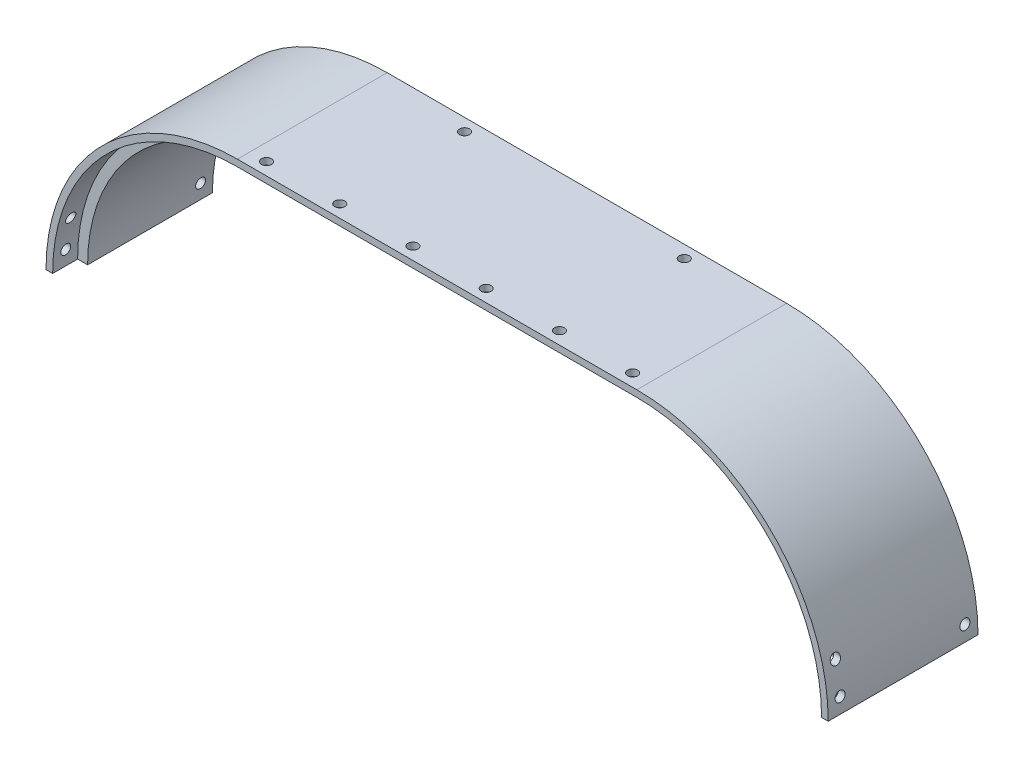
SolidWorks part; units mm, degrees
ref_plane "Front Plane" through (0, 0, 0) normal (0, 0, 1) x (1, 0, 0)
ref_plane "Top Plane" through (0, 0, 0) normal (0, 1, 0) x (1, 0, 0)
ref_plane "Right Plane" through (0, 0, 0) normal (1, 0, 0) x (0, 0, -1)
sketch "Sketch1" plane through (0, 0, 0) normal (0, 0, 1) x (1, 0, 0)
  line L0 (-60, 52.5) -> (60, 52.5)
  line L1 (-60, -52.5) -> (60, -52.5)
  line L2 (-60, 57.5) -> (60, 57.5)
  line L3 (-60, -57.5) -> (60, -57.5)
  line L4 (-130.8088, 0) -> (140.4694, 0)
  arc A0 (-60, 52.5) -> (-60, -52.5) centre (-60, 0) ccw
  arc A1 (60, -52.5) -> (60, 52.5) centre (60, 0) ccw
  arc A2 (60, 52.5) -> (60, -52.5) centre (60, 0) ccw construction
  arc A3 (-60, -52.5) -> (-60, 52.5) centre (-60, 0) ccw construction
  arc A4 (60, -57.5) -> (60, 57.5) centre (60, 0) ccw
  arc A5 (-60, 57.5) -> (-60, -57.5) centre (-60, 0) ccw
  dimension "D1" = 105
  dimension "D2" = 60
  dimension "D3" = 60
  dimension "D4" = 5
extrude "Boss-Extrude1" add sketch "Sketch1" along normal blind 45 contours L2 A5 L4 A0 L0 A1 A4
sketch "Sketch3" plane through (0, 0, 45) normal (0, 0, 1) x (1, 0, 0)
  line L4 (-115.5, 0) -> (115.5, 0)
  line L5 (60, 55.5) -> (-60, 55.5)
  line L6 (60, 55.5) -> (-60, 55.5)
  arc A10 (115.5, 0) -> (60, 55.5) centre (60, 0) ccw
  arc A11 (-60, 55.5) -> (-115.5, 0) centre (-60, 0) ccw
  arc A12 (115.5, 0) -> (60, 55.5) centre (60, 0) ccw
  arc A13 (-60, 55.5) -> (-115.5, 0) centre (-60, 0) ccw
  dimension "D1" = 3
extrude "Cut-Extrude1" cut sketch "Sketch3" against normal blind 7.5
sketch "Sketch4" plane through (0, 57.5, 0) normal (0, 1, 0) x (1, 0, 0)
  line L0 (0, -65.2933) -> (0, 28.2975) construction
  line L1 (-60, 0) -> (60, 0) construction
  line L2 (-60, -45) -> (60, -45) construction
  circle A0 centre (33, -3.75) radius 1.5
  circle A1 centre (11, -41.25) radius 1.5
  circle A2 centre (33, -41.25) radius 1.5
  circle A3 centre (55, -41.25) radius 1.5
  circle A4 centre (-33, -3.75) radius 1.5
  circle A5 centre (-11, -41.25) radius 1.5
  circle A6 centre (-33, -41.25) radius 1.5
  circle A7 centre (-55, -41.25) radius 1.5
  dimension "D1" = 3
  dimension "D4" = 3
  dimension "D2" = 3.75
  dimension "D3" = 33
  dimension "D5" = 3.75
  dimension "D6" = 11
  dimension "D7" = 3
extrude "Cut-Extrude2" cut sketch "Sketch4" against normal blind 7.5
sketch "Sketch5" plane through (0, 0, 0) normal (1, 0, 0) x (0, 0, -1)
  line L0 (0, 0) -> (0, 57.5) construction
  line L1 (-45, 0) -> (0, 0) construction
  line L2 (-45, 57.5) -> (-45, 0) construction
  circle A0 centre (-3.75, 4.5) radius 1.5
  circle A1 centre (-41.25, 4.5) radius 1.5
  circle A2 centre (-41.25, 13.5) radius 1.5
  point P10 (0, 0)
  point P13 (0, 0)
  dimension "D1" = 3
  dimension "D2" = 3
  dimension "D3" = 3
  dimension "D4" = 3.75
  dimension "D5" = 4.5
  dimension "D6" = 3.75
  dimension "D7" = 9
extrude "Cut-Extrude3" cut sketch "Sketch5" against normal through all both and the other way through all
